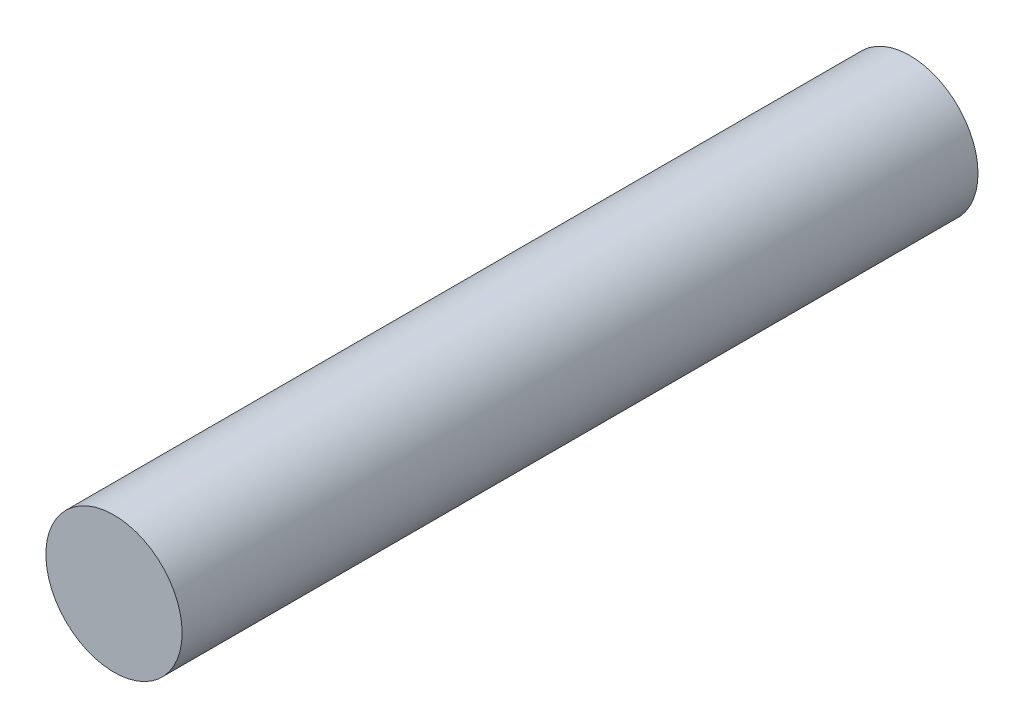
SolidWorks part; units mm, degrees
ref_plane "Front Plane" through (0, 0, 0) normal (0, 0, 1) x (1, 0, 0)
ref_plane "Top Plane" through (0, 0, 0) normal (0, 1, 0) x (1, 0, 0)
ref_plane "Right Plane" through (0, 0, 0) normal (1, 0, 0) x (0, 0, -1)
sketch "Sketch2" plane through (0, 0, 0) normal (0, 0, 1) x (1, 0, 0)
  circle A0 centre (0, 0) radius 1.3589
  point P2 (0, 0)
  point P4 (0, 0)
  dimension "D1" = 2.7178
extrude "Boss-Extrude1" add sketch "Sketch2" along normal blind 15.875
